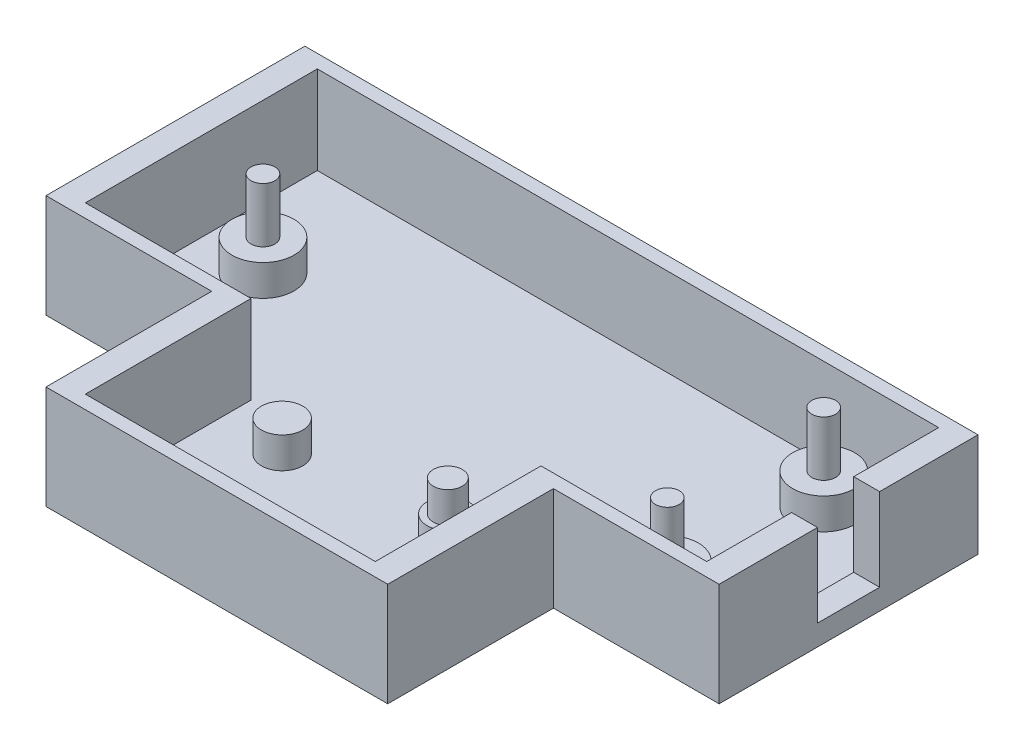
SolidWorks part; units mm, degrees
ref_plane "Alzado" through (0, 0, 0) normal (0, 0, 1) x (1, 0, 0)
ref_plane "Planta" through (0, 0, 0) normal (0, 1, 0) x (1, 0, 0)
ref_plane "Vista lateral" through (0, 0, 0) normal (1, 0, 0) x (0, 0, -1)
sketch "Croquis1" plane through (0, 0, 0) normal (0, 1, 0) x (1, 0, 0)
  line L1 (32.5, -12.5) -> (-32.5, -12.5)
  line L2 (32.5, -12.5) -> (32.5, 12.5)
  line L3 (32.5, 12.5) -> (-32.5, 12.5)
  line L4 (-32.5, -12.5) -> (-32.5, 12.5)
  line L5 (32.5, -12.5) -> (-32.5, 12.5) construction
  line L6 (32.5, 12.5) -> (-32.5, -12.5) construction
  point P0 (0, 0)
  dimension "D1" = 65
  dimension "D2" = 25
extrude "Saliente-Extruir1" add sketch "Croquis1" along normal blind 10
sketch "Croquis2" plane through (0, 10, 0) normal (0, 1, 0) x (1, 0, 0)
  line L0 (32.5, -12.5) -> (32.5, 12.5) construction
  line L1 (30, -11.2) -> (-30, -11.2)
  line L2 (30, -11.2) -> (30, 11.2)
  line L3 (30, 11.2) -> (-30, 11.2)
  line L4 (-30, -11.2) -> (-30, 11.2)
  line L5 (30, -11.2) -> (-30, 11.2) construction
  line L6 (30, 11.2) -> (-30, -11.2) construction
  line L7 (32.5, 12.5) -> (-32.5, 12.5) construction
  point P0 (0, 0)
  dimension "D1" = 2.5
  dimension "D2" = 1.3
extrude "Cortar-Extruir1" cut sketch "Croquis2" against normal blind 8.5
sketch "Sketch3" plane through (0, 1.5, 0) normal (0, 1, 0) x (1, 0, 0)
  line L0 (30, 0) -> (-30, 0) construction
  line L1 (30, -11.2) -> (30, 11.2) construction
  line L2 (-30, 11.2) -> (-30, -11.2) construction
  line L3 (22.55, 11.2) -> (22.55, -11.2) construction
  line L4 (30, 11.2) -> (-30, 11.2) construction
  line L5 (-30, -11.2) -> (30, -11.2) construction
  circle A0 centre (-24.05, 0) radius 3
  circle A1 centre (22.55, 7.55) radius 3
  circle A2 centre (22.55, -7.55) radius 3
  dimension "D2" = 6
  dimension "D4" = 6
  dimension "D1" = 5.95
  dimension "D3" = 7.45
  dimension "D5" = 3.65
extrude "Boss-Extrude3" add sketch "Sketch3" along normal blind 3
sketch "Sketch4" plane through (0, 4.5, 0) normal (0, 1, 0) x (1, 0, 0)
  circle A0 centre (-24.05, 0) radius 1.15
  circle A1 centre (22.55, 7.55) radius 1.15
  circle A2 centre (22.55, -7.55) radius 1.15
  dimension "D1" = 2.3
extrude "Boss-Extrude4" add sketch "Sketch4" along normal blind 5.3
sketch "Croquis3" plane through (0, 0, 0) normal (0, -1, 0) x (1, 0, 0)
  line L0 (32.5, 0) -> (-32.5, 0) construction
  line L1 (32.5, 12.5) -> (32.5, -12.5) construction
  line L2 (-32.5, -12.5) -> (-32.5, 12.5) construction
  line L3 (0, 12.5) -> (0, -12.5) construction
  line L4 (-32.5, 12.5) -> (32.5, 12.5) construction
  line L5 (32.5, -12.5) -> (-32.5, -12.5) construction
  line L6 (21.5, 10.5) -> (29.5, 6.5) construction
  line L7 (-21.5, 6.5) -> (-29.5, 6.5)
  line L8 (-21.5, 6.5) -> (-21.5, 10.5)
  line L9 (-21.5, 10.5) -> (-29.5, 10.5)
  line L10 (-29.5, 6.5) -> (-29.5, 10.5)
  line L11 (-21.5, 6.5) -> (-29.5, 10.5) construction
  line L12 (-21.5, 10.5) -> (-29.5, 6.5) construction
  line L13 (21.5, 6.5) -> (29.5, 10.5) construction
  line L14 (29.5, 6.5) -> (29.5, 10.5)
  line L15 (21.5, 10.5) -> (29.5, 10.5)
  line L16 (21.5, 6.5) -> (21.5, 10.5)
  line L17 (21.5, 6.5) -> (29.5, 6.5)
  line L18 (-21.5, -10.5) -> (-29.5, -6.5) construction
  line L19 (-21.5, -6.5) -> (-29.5, -10.5) construction
  line L20 (-29.5, -6.5) -> (-29.5, -10.5)
  line L21 (-21.5, -10.5) -> (-29.5, -10.5)
  line L22 (-21.5, -6.5) -> (-21.5, -10.5)
  line L23 (-21.5, -6.5) -> (-29.5, -6.5)
  line L24 (21.5, -6.5) -> (29.5, -10.5) construction
  line L25 (21.5, -10.5) -> (29.5, -6.5) construction
  line L26 (21.5, -6.5) -> (29.5, -6.5)
  line L27 (21.5, -6.5) -> (21.5, -10.5)
  line L28 (21.5, -10.5) -> (29.5, -10.5)
  line L29 (29.5, -6.5) -> (29.5, -10.5)
  point P12 (-25.5, 8.5)
  point P21 (25.5, 8.5)
  point P26 (-25.5, -8.5)
  point P31 (25.5, -8.5)
  dimension "D1" = 8
  dimension "D2" = 4
  dimension "D3" = 3
  dimension "D4" = 2
ref_plane "Plano1" through (0, 0, 0) normal (0, 0, 1) x (1, 0, 0)
sketch "Croquis5" plane through (32.5, 0, 0) normal (1, 0, 0) x (0, 0, -1)
  line L0 (-12.5, 5) -> (12.5, 5) construction
  line L1 (-12.5, 10) -> (-12.5, 0) construction
  line L2 (12.5, 10) -> (12.5, 0) construction
  line L3 (0, 10) -> (0, 0) construction
  line L4 (-12.5, 10) -> (12.5, 10) construction
  line L6 (-3, 10) -> (3, 10)
  line L7 (-3, 10) -> (-3, 2)
  line L8 (-3, 2) -> (3, 2)
  line L9 (3, 10) -> (3, 2)
  dimension "D1" = 8
  dimension "D2" = 3
  dimension "D3" = 3
extrude "Cortar-Extruir3" cut sketch "Croquis5" against normal up to next
sketch "Croquis12" plane through (0, 0, 0) normal (0, 1, 0) x (1, 0, 0)
  line L0 (0, 0) -> (0, -35.6213) construction
  line L1 (-32.5, -12.5) -> (32.5, -12.5) construction
  line L2 (16.5, -28.5) -> (-16.5, -28.5)
  line L3 (16.5, -28.5) -> (16.5, -12.5)
  line L4 (16.5, -12.5) -> (-16.5, -12.5)
  line L5 (-16.5, -28.5) -> (-16.5, -12.5)
  line L6 (16.5, -28.5) -> (-16.5, -12.5) construction
  line L7 (16.5, -12.5) -> (-16.5, -28.5) construction
  point P3 (0, -20.5)
  dimension "D1" = 33
  dimension "D2" = 16
extrude "Saliente-Extruir7" add sketch "Croquis12" along normal blind 10
sketch "Croquis13" plane through (0, 10, 0) normal (0, 1, 0) x (1, 0, 0)
  line L0 (-16.5, -12.5) -> (-16.5, -28.5) construction
  line L1 (-14, -11.2) -> (14, -11.2)
  line L2 (-14, -11.2) -> (-14, -27.2)
  line L3 (-14, -27.2) -> (14, -27.2)
  line L4 (14, -11.2) -> (14, -27.2)
  line L5 (-30, -11.2) -> (30, -11.2) construction
  line L6 (-16.5, -28.5) -> (16.5, -28.5) construction
  line L7 (16.5, -28.5) -> (16.5, -12.5) construction
  dimension "D1" = 2.5
  dimension "D2" = 1.3
  dimension "D3" = 2.5
extrude "Cortar-Extruir6" cut sketch "Croquis13" against normal up to surface (8.5 mm away) up to face at (22.55, 1.5, 4.55)
sketch "Croquis14" plane through (0, 1.5, 0) normal (0, 1, 0) x (1, 0, 0)
  line L0 (14, -11.2) -> (30, -11.2) construction
  line L1 (32.5, -12.5) -> (32.5, -3) construction
  line L2 (14, -19.2) -> (-14, -19.2) construction
  line L3 (14, -11.2) -> (14, -27.2) construction
  line L4 (-14, -27.2) -> (-14, -11.2) construction
  line L5 (0, -27.2) -> (0, -11.1948) construction
  line L6 (-14, -27.2) -> (14, -27.2) construction
  circle A0 centre (8, -14.2) radius 2
  circle A1 centre (8, -24.2) radius 2
  circle A2 centre (-8, -24.2) radius 2
  circle A3 centre (-8, -14.2) radius 2
  dimension "D1" = 4
  dimension "D2" = 3
  dimension "D3" = 24.5
extrude "Saliente-Extruir8" add sketch "Croquis14" along normal blind 3
sketch "Croquis15" plane through (0, 4.5, 0) normal (0, 1, 0) x (1, 0, 0)
  circle A0 centre (8, -14.2) radius 1.4
  dimension "D1" = 2.8
extrude "Saliente-Extruir9" add sketch "Croquis15" along normal blind 3
